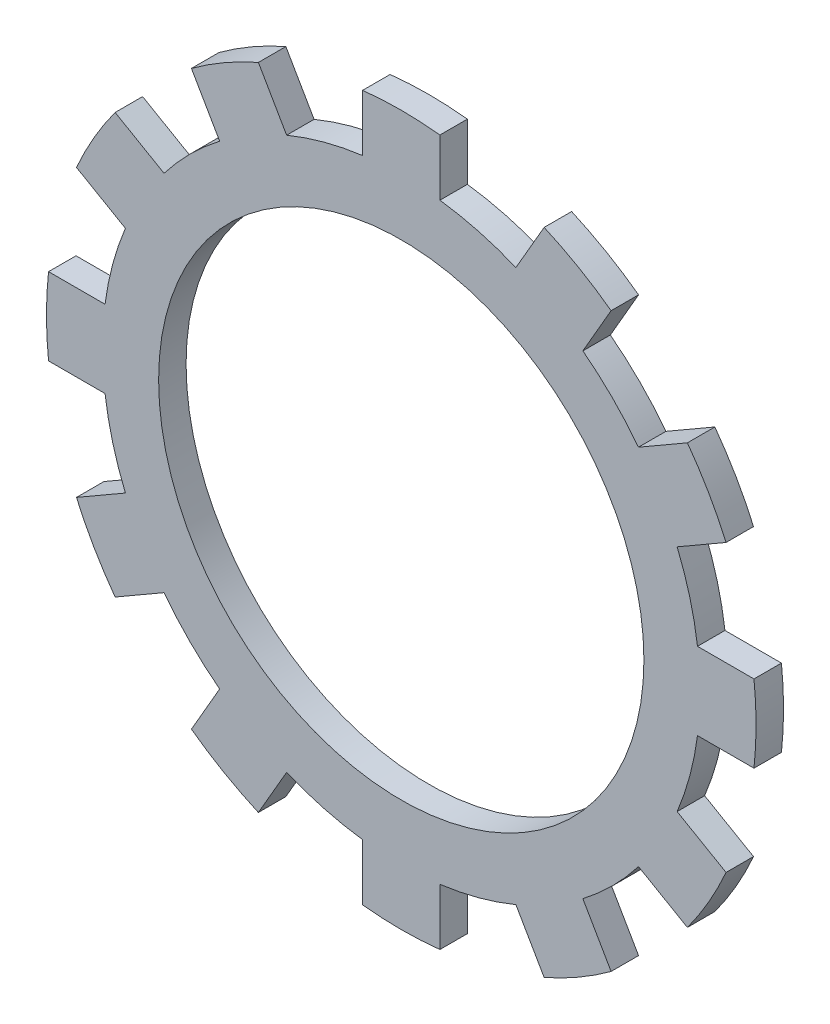
SolidWorks part; units mm, degrees
ref_plane "Front Plane" through (0, 0, 0) normal (0, 0, 1) x (1, 0, 0)
ref_plane "Top Plane" through (0, 0, 0) normal (0, 1, 0) x (1, 0, 0)
ref_plane "Right Plane" through (0, 0, 0) normal (1, 0, 0) x (0, 0, -1)
sketch "Sketch1" plane through (0, 0, 0) normal (0, 0, 1) x (1, 0, 0)
  circle A0 centre (0, 0) radius 15.5 construction
  circle A1 centre (0, 0) radius 10.6
  circle A2 centre (0, 0) radius 13.05
  dimension "D1" = 26.1
  dimension "A" = 21.2
  dimension "B" = 31
extrude "Extrude1" add sketch "Sketch1" along normal blind 1.2
sketch "Sketch2" plane through (0, 0, 0) normal (0, 0, 1) x (1, 0, 0)
  line L0 (0, 0) -> (0, 15.5) construction
  line L1 (0, 0) -> (4.0117, 14.9719) construction
  line L2 (0, 0) -> (-4.0117, 14.9719) construction
  line L3 (-3.3776, 12.6053) -> (0, 12.6053) construction
  line L4 (-1.6888, 15.4077) -> (-1.6888, 12.9403)
  line L5 (1.6888, 15.4077) -> (1.6888, 12.9403)
  line L6 (-1.6888, 12.9403) -> (1.6888, 12.9403)
  circle A0 centre (0, 0) radius 13.05 construction
  circle A1 centre (0, 0) radius 13.05 construction
  circle A2 centre (0, 0) radius 15.5 construction
  arc A3 (1.6888, 15.4077) -> (-1.6888, 15.4077) centre (0, 0) ccw
  dimension "D2" = 15
  dimension "D3" = 15
extrude "Extrude2" add sketch "Sketch2" along normal up to surface (1.2 mm away) up to face at (13.05, 0, 1.2)
pattern_circular "CirPattern1" count 12 over 360 about axis through (0, 0, 0) along (0, 0, 1) of "Extrude2"
sketch "Sketch3" plane through (0, 0, 0) normal (0, 0, 1) x (1, 0, 0)
  line L0 (-2.0163, 15.3683) -> (-2.0163, 12.8933)
  line L1 (2.0163, 15.3683) -> (2.0163, 12.8933)
  line L2 (0, 0) -> (0, 15.5) construction
  line L3 (0, 0) -> (4.7898, 14.7414) construction
  line L4 (0, 0) -> (-4.7898, 14.7414) construction
  line L5 (-4.0327, 12.4113) -> (0, 12.4113) construction
  line L6 (-2.0163, 12.8933) -> (2.0163, 12.8933)
  circle A0 centre (0, 0) radius 15.5 construction
  circle A1 centre (0, 0) radius 13.05 construction
  circle A2 centre (0, 0) radius 13.05 construction
  arc A3 (2.0163, 15.3683) -> (-2.0163, 15.3683) centre (0, 0) ccw
  dimension "D2" = 18
  dimension "D3" = 18
extrude "Extrude3" [suppressed] add sketch "Sketch3" along normal up to surface (0.25 mm away)
pattern_circular "CirPattern2" [suppressed] count 10 over 360
equation "\"D1@Sketch1\" =  ( \"B@Sketch1\" + \"A@Sketch1\" )  / 2"
